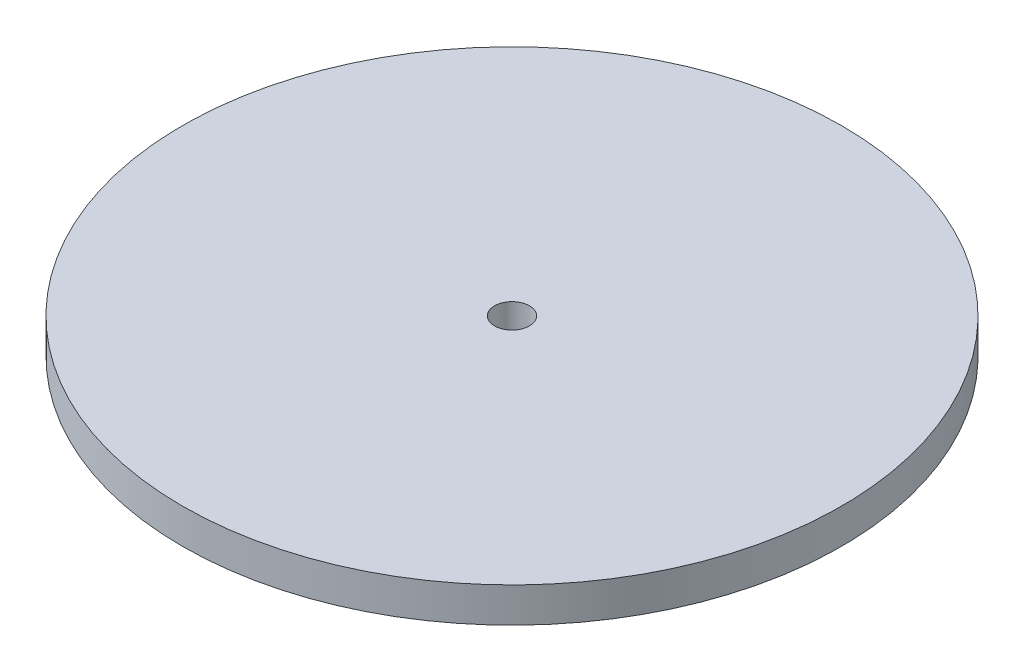
SolidWorks part; units mm, degrees
ref_plane "Front Plane" through (0, 0, 0) normal (0, 0, 1) x (1, 0, 0)
ref_plane "Top Plane" through (0, 0, 0) normal (0, 1, 0) x (1, 0, 0)
ref_plane "Right Plane" through (0, 0, 0) normal (1, 0, 0) x (0, 0, -1)
sketch "Sketch1" plane through (0, 0, 0) normal (0, 1, 0) x (1, 0, 0)
  circle A0 centre (0, 0) radius 37.8
  circle A1 centre (0, 0) radius 2
  dimension "D1" = 75.6
  dimension "D2" = 4
extrude "Boss-Extrude1" add sketch "Sketch1" along normal blind 4
